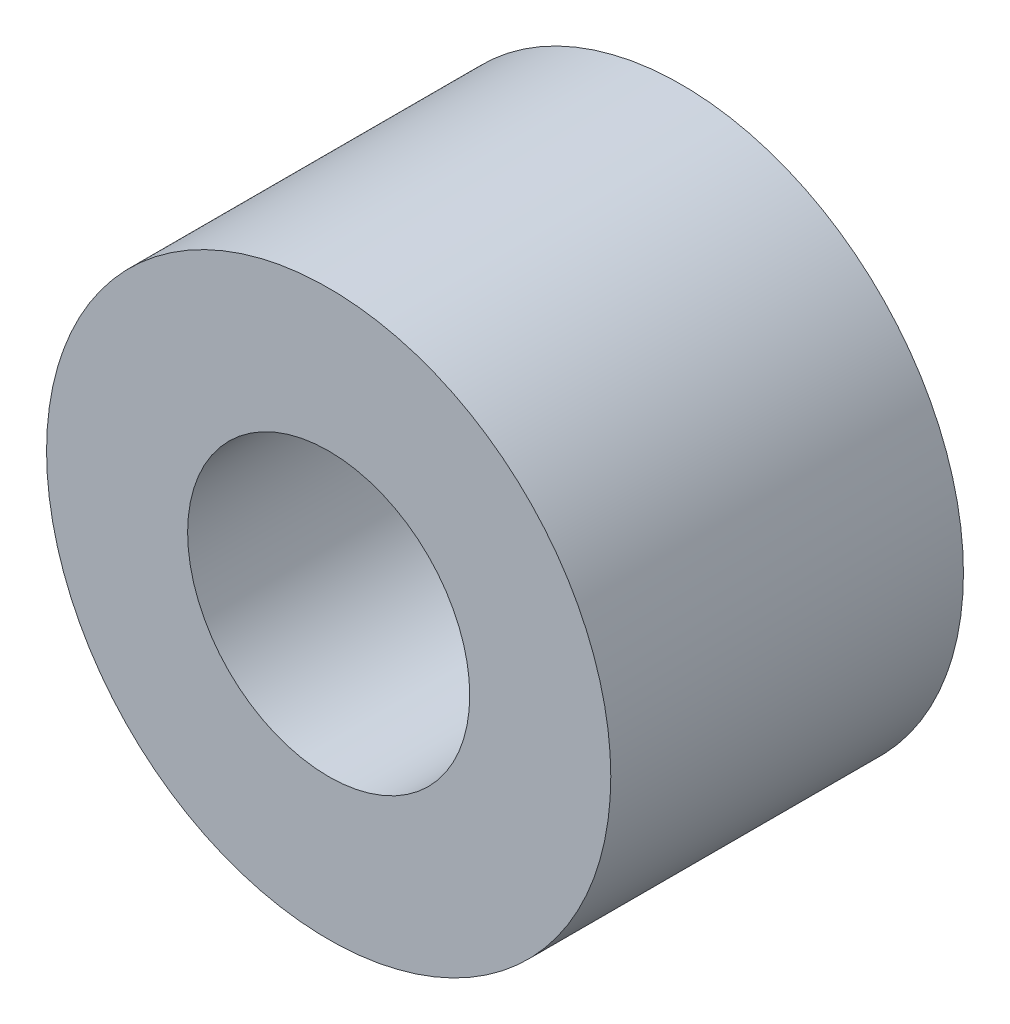
SolidWorks part; units mm, degrees
ref_plane "Front Plane" through (0, 0, 0) normal (0, 0, 1) x (1, 0, 0)
ref_plane "Top Plane" through (0, 0, 0) normal (0, 1, 0) x (1, 0, 0)
ref_plane "Right Plane" through (0, 0, 0) normal (1, 0, 0) x (0, 0, -1)
sketch "Sketch1" plane through (0, 0, 0) normal (0, 0, 1) x (1, 0, 0)
  circle A0 centre (0, 0) radius 1
  circle A1 centre (0, 0) radius 2
extrude "Boss-Extrude1" add sketch "Sketch1" along normal blind 2.5
